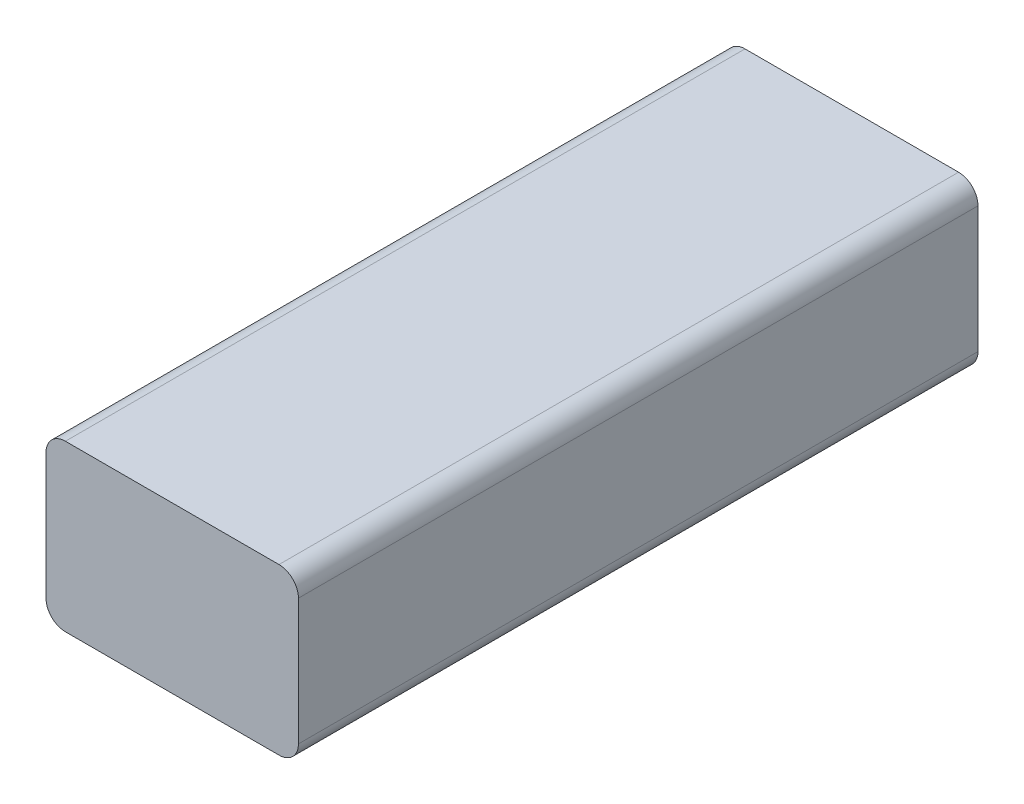
SolidWorks part; units mm, degrees
ref_plane "Płaszczyzna przednia" through (0, 0, 0) normal (0, 0, 1) x (1, 0, 0)
ref_plane "Płaszczyzna górna" through (0, 0, 0) normal (0, 1, 0) x (1, 0, 0)
ref_plane "Płaszczyzna prawa" through (0, 0, 0) normal (1, 0, 0) x (0, 0, -1)
sketch "Szkic1" plane through (0, 0, 0) normal (0, 0, 1) x (1, 0, 0)
  line L1 (-7.3064, 7.1152) -> (14.6936, 7.1152)
  line L2 (-9.3064, 5.1152) -> (-9.3064, -7.8848)
  line L3 (-7.3064, -9.8848) -> (14.6936, -9.8848)
  line L4 (16.6936, 5.1152) -> (16.6936, -7.8848)
  arc A0 (14.6936, -9.8848) -> (16.6936, -7.8848) centre (14.6936, -7.8848) ccw
  arc A1 (-9.3064, -7.8848) -> (-7.3064, -9.8848) centre (-7.3064, -7.8848) ccw
  arc A2 (-7.3064, 7.1152) -> (-9.3064, 5.1152) centre (-7.3064, 5.1152) ccw
  arc A3 (14.6936, 7.1152) -> (16.6936, 5.1152) centre (14.6936, 5.1152) cw
  point P6 (16.6936, -9.8848)
  point P11 (-9.3064, 7.1152)
  point P14 (16.6936, 7.1152)
  dimension "D3" = 2
  dimension "D1" = 26
  dimension "D2" = 17
extrude "Dodanie-wyciągnięcie1" add sketch "Szkic1" along normal blind 70
